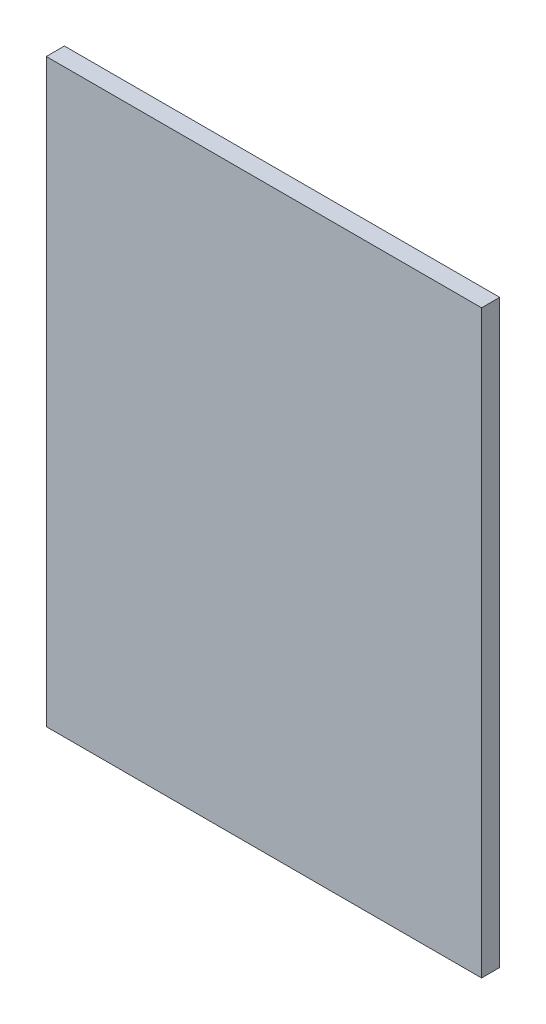
SolidWorks part; units mm, degrees
ref_plane "Front Plane" through (0, 0, 0) normal (0, 0, 1) x (1, 0, 0)
ref_plane "Top Plane" through (0, 0, 0) normal (0, 1, 0) x (1, 0, 0)
ref_plane "Right Plane" through (0, 0, 0) normal (1, 0, 0) x (0, 0, -1)
sketch "Sketch1" plane through (0, 0, 0) normal (0, 0, 1) x (1, 0, 0)
  line L1 (0, 0) -> (304.8, 0)
  line L2 (0, 0) -> (0, 406.4)
  line L3 (0, 406.4) -> (304.8, 406.4)
  line L4 (304.8, 0) -> (304.8, 406.4)
  dimension "D1" = 304.8
  dimension "D2" = 406.4
extrude "Boss-Extrude1" add sketch "Sketch1" along normal blind 12.7
